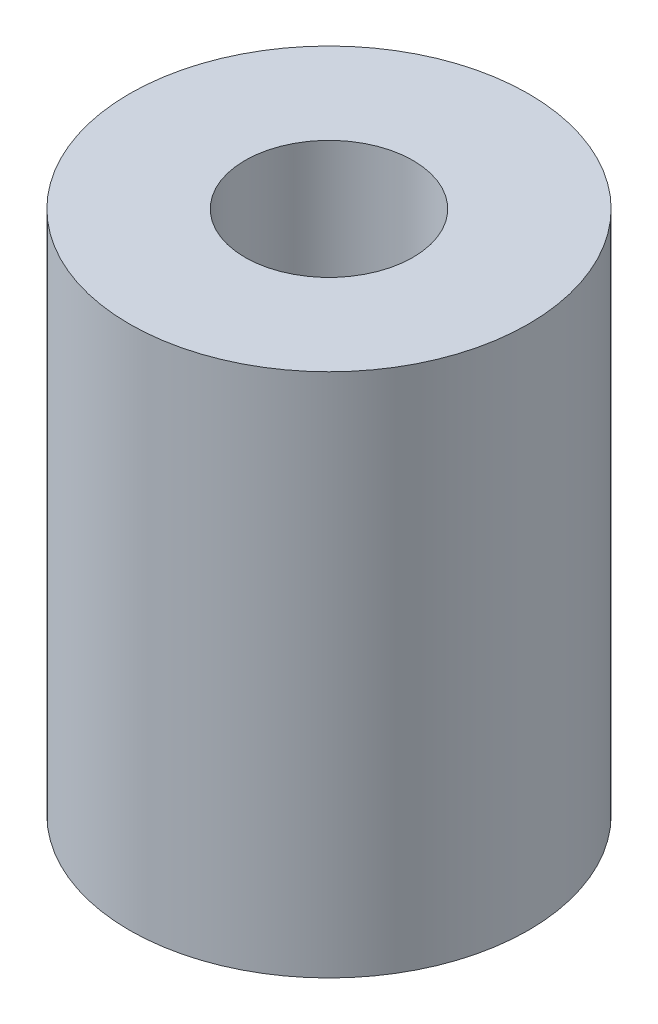
SolidWorks part; units mm, degrees
ref_plane "Front Plane" through (0, 0, 0) normal (0, 0, 1) x (1, 0, 0)
ref_plane "Top Plane" through (0, 0, 0) normal (0, 1, 0) x (1, 0, 0)
ref_plane "Right Plane" through (0, 0, 0) normal (1, 0, 0) x (0, 0, -1)
sketch "Sketch1" plane through (0, 0, 0) normal (0, 1, 0) x (1, 0, 0)
  circle A0 centre (0, 0) radius 9.5
  dimension "D1" = 19
extrude "Boss-Extrude1" add sketch "Sketch1" along normal blind 25
sketch "Sketch2" plane through (0, 25, 0) normal (0, 1, 0) x (1, 0, 0)
  circle A0 centre (0, 0) radius 4
  dimension "D1" = 8
extrude "Cut-Extrude1" cut sketch "Sketch2" against normal blind 12.5
sketch "Sketch3" plane through (0, 0, 0) normal (0, -1, 0) x (1, 0, 0)
  circle A0 centre (0, 0) radius 2.5
  dimension "D1" = 5
extrude "Cut-Extrude2" cut sketch "Sketch3" against normal blind 12.5
